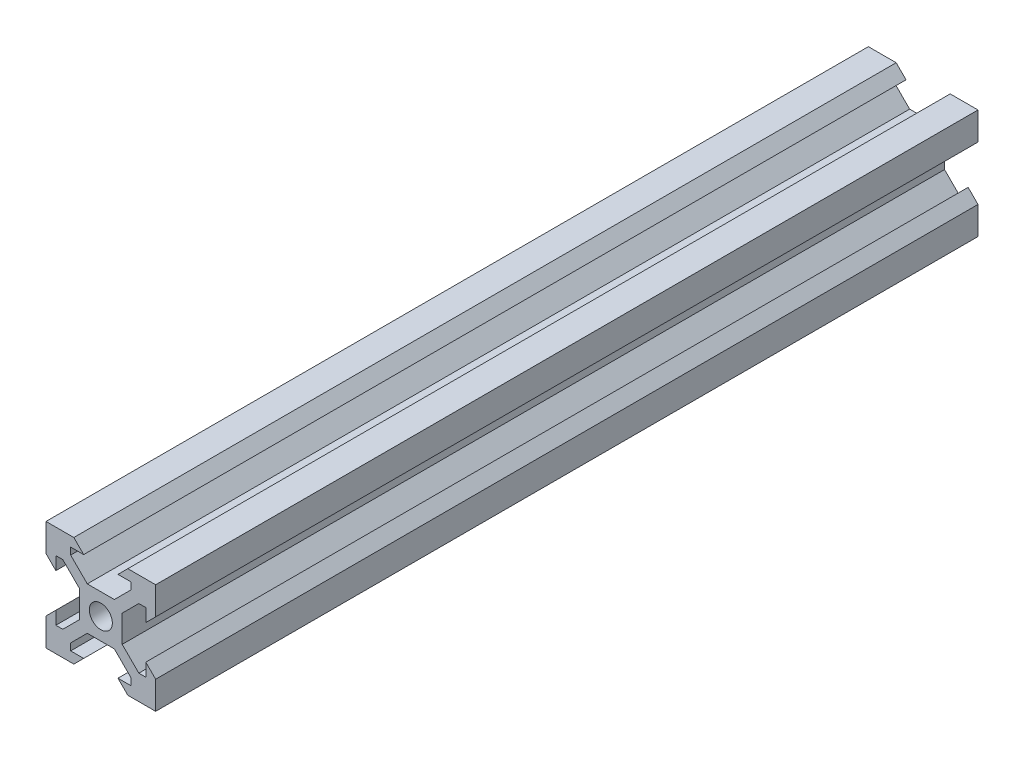
SolidWorks part; units mm, degrees
ref_plane "Front Plane" through (0, 0, 0) normal (0, 0, 1) x (1, 0, 0)
ref_plane "Top Plane" through (0, 0, 0) normal (0, 1, 0) x (1, 0, 0)
ref_plane "Right Plane" through (0, 0, 0) normal (1, 0, 0) x (0, 0, -1)
sketch "Sketch1" plane through (0, 0, 0) normal (0, 0, 1) x (1, 0, 0)
  line L0 (-19.9727, 0) -> (16.5027, 0) construction
  line L1 (-10, -10) -> (10, -10)
  line L2 (-10, -10) -> (-10, 10)
  line L3 (-10, 10) -> (10, 10)
  line L4 (10, -10) -> (10, 10)
  line L5 (-10, -10) -> (10, 10) construction
  line L6 (-10, 10) -> (10, -10) construction
  line L7 (55, 0) -> (-55, 0) construction
  line L8 (0, 14.8997) -> (0, -15.8051) construction
  line L9 (0, -55) -> (0, 55) construction
  line L10 (-4.925, 10) -> (-3.125, 8.2)
  line L11 (-3.125, 8.2) -> (-5.5, 8.2)
  line L12 (-5.5, 8.2) -> (-5.5, 6.9332)
  line L13 (-2.4668, 3.9) -> (2.4668, 3.9)
  line L14 (-5.5, 6.9332) -> (-2.4668, 3.9)
  line L15 (5.5, 6.9332) -> (2.4668, 3.9)
  line L16 (5.5, 8.2) -> (5.5, 6.9332)
  line L17 (3.125, 8.2) -> (5.5, 8.2)
  line L18 (4.925, 10) -> (3.125, 8.2)
  line L19 (10, 4.925) -> (8.2, 3.125)
  line L20 (8.2, 3.125) -> (8.2, 5.5)
  line L21 (8.2, 5.5) -> (6.9332, 5.5)
  line L22 (6.9332, 5.5) -> (3.9, 2.4668)
  line L23 (3.9, -2.4668) -> (3.9, 2.4668)
  line L24 (6.9332, -5.5) -> (3.9, -2.4668)
  line L25 (8.2, -5.5) -> (6.9332, -5.5)
  line L26 (8.2, -3.125) -> (8.2, -5.5)
  line L27 (10, -4.925) -> (8.2, -3.125)
  line L28 (4.925, -10) -> (3.125, -8.2)
  line L29 (-10, 10) -> (-10, -10)
  line L30 (10, -10) -> (-10, -10)
  line L31 (10, 10) -> (10, -10)
  line L32 (10, 10) -> (-10, 10)
  line L33 (3.125, -8.2) -> (5.5, -8.2)
  line L34 (5.5, -8.2) -> (5.5, -6.9332)
  line L35 (5.5, -6.9332) -> (2.4668, -3.9)
  line L36 (2.4668, -3.9) -> (-2.4668, -3.9)
  line L37 (-4.925, -10) -> (-3.125, -8.2)
  line L38 (-3.125, -8.2) -> (-5.5, -8.2)
  line L39 (-5.5, -8.2) -> (-5.5, -6.9332)
  line L40 (-5.5, -6.9332) -> (-2.4668, -3.9)
  line L41 (-10, 4.925) -> (-8.2, 3.125)
  line L42 (-8.2, 3.125) -> (-8.2, 5.5)
  line L43 (-8.2, 5.5) -> (-6.9332, 5.5)
  line L44 (-6.9332, 5.5) -> (-3.9, 2.4668)
  line L45 (-3.9, 2.4668) -> (-3.9, -2.4668)
  line L46 (-6.9332, -5.5) -> (-3.9, -2.4668)
  line L47 (-8.2, -5.5) -> (-6.9332, -5.5)
  line L48 (-8.2, -3.125) -> (-8.2, -5.5)
  line L49 (-10, -4.925) -> (-8.2, -3.125)
  circle A0 centre (0, 0) radius 2.1
  point P0 (0, 0)
  point P21 (0, 3.9)
  dimension "D9" = 4.2
  dimension "D2" = 20
  dimension "D3" = 1.8
  dimension "D4" = 3.125
  dimension "D5" = 45
  dimension "D6" = 4.3
  dimension "D7" = 5.5
  dimension "D8" = 45
extrude "Boss-Extrude1" add sketch "Sketch1" along normal mid plane 150 contours L49 L2 L1 L37 L38 L39 L40 L36 L35 L34 L33 L28 L4 L27 L26 L25 L24 L23 L22 L21 L20 L19 L3 L18 L17 L16 L15 L13 L14 L12 L11 L10 L29 L41 L42 L43 L44 L45 L46 L47 L48 A0
